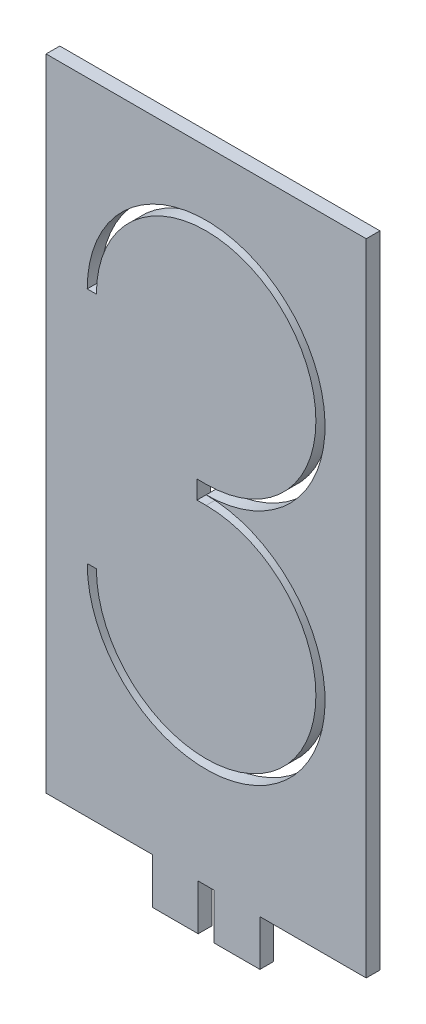
SolidWorks part; units mm, degrees
material "Glas"
ref_plane "Ebene vorne" through (0, 0, 0) normal (0, 0, 1) x (1, 0, 0)
ref_plane "Ebene oben" through (0, 0, 0) normal (0, 1, 0) x (1, 0, 0)
ref_plane "Ebene rechts" through (0, 0, 0) normal (1, 0, 0) x (0, 0, -1)
sketch "Skizze1" plane through (0, 0, 0) normal (0, 0, 1) x (1, 0, 0)
  line L1 (0, 0) -> (35, 0)
  line L2 (0, 0) -> (0, 75)
  line L3 (0, 75) -> (35, 75)
  line L4 (35, 0) -> (35, 75)
  dimension "D1" = 35
  dimension "D2" = 75
extrude "Aufsatz-Linear austragen1" add sketch "Skizze1" along normal blind 1.5
sketch "Skizze2" plane through (0, 0, 1.5) normal (0, 0, 1) x (1, 0, 0)
  line L0 (0, 0) -> (35, 0) construction
  line L1 (0, 0) -> (11.63, 0)
  line L2 (0, 0) -> (0, 5)
  line L3 (0, 5) -> (11.63, 5)
  line L4 (11.63, 0) -> (11.63, 5)
  line L5 (23.38, 5) -> (35, 5)
  line L6 (23.38, 5) -> (23.38, 0)
  line L7 (23.38, 0) -> (35, 0)
  line L8 (35, 5) -> (35, 0)
  line L9 (16.63, 0) -> (18.38, 0)
  line L10 (16.63, 0) -> (16.63, 5)
  line L11 (16.63, 5) -> (18.38, 5)
  line L12 (18.38, 0) -> (18.38, 5)
  dimension "D1" = 5
  dimension "D2" = 5
  dimension "D3" = 5
  dimension "D4" = 11.63
  dimension "D5" = 1.75
  dimension "D6" = 5
extrude "Schnitt-Linear austragen1" cut sketch "Skizze2" against normal blind 1.5
sketch "Skizze9" plane through (0, 0, 1.5) normal (0, 0, 1) x (1, 0, 0)
  line L0 (35, 75) -> (0, 75) construction
  line L1 (35, 5) -> (35, 75) construction
  line L2 (5.5, 55) -> (4.5, 55)
  line L3 (5.5, 29) -> (4.5, 29)
  line L4 (16.5, 43) -> (16.5, 41)
  line L5 (16.5, 41) -> (17.5, 41)
  line L6 (16.5, 43) -> (17.5, 43)
  arc A0 (4.5, 55) -> (17.5, 42) centre (17.5, 55) cw
  arc A1 (17.5, 42) -> (4.5, 29) centre (17.5, 29) cw
  arc A2 (5.5, 29) -> (17.5, 41) centre (17.5, 29) ccw
  arc A3 (5.5, 55) -> (17.5, 43) centre (17.5, 55) cw
  dimension "D1" = 13
  dimension "D2" = 13
  dimension "D4" = 17.5
  dimension "D5" = 1
  dimension "D3" = 20
extrude "Schnitt-Linear austragen4" cut sketch "Skizze9" against normal blind 20
